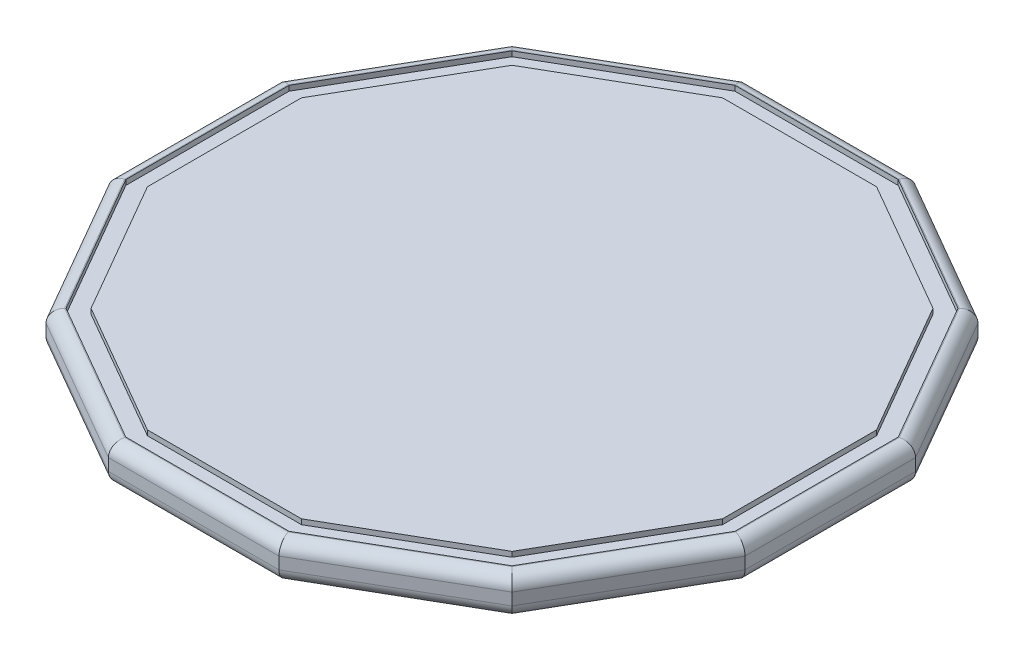
SolidWorks part; units mm, degrees
ref_plane "정면" through (0, 0, 0) normal (0, 0, 1) x (1, 0, 0)
ref_plane "윗면" through (0, 0, 0) normal (0, 1, 0) x (1, 0, 0)
ref_plane "우측면" through (0, 0, 0) normal (1, 0, 0) x (0, 0, -1)
sketch "스케치1" plane through (0, 0, 0) normal (0, 1, 0) x (1, 0, 0)
  line L1 (27.2932, -27.2932) -> (37.2832, -9.99)
  line L2 (37.2832, -9.99) -> (37.2832, 9.99)
  line L3 (37.2832, 9.99) -> (27.2932, 27.2932)
  line L4 (27.2932, 27.2932) -> (9.99, 37.2832)
  line L5 (9.99, 37.2832) -> (-9.99, 37.2832)
  line L6 (-9.99, 37.2832) -> (-27.2932, 27.2932)
  line L7 (-27.2932, 27.2932) -> (-37.2832, 9.99)
  line L8 (-37.2832, 9.99) -> (-37.2832, -9.99)
  line L9 (-37.2832, -9.99) -> (-27.2932, -27.2932)
  line L10 (-27.2932, -27.2932) -> (-9.99, -37.2832)
  line L11 (-9.99, -37.2832) -> (9.99, -37.2832)
  line L12 (9.99, -37.2832) -> (27.2932, -27.2932)
  circle A0 centre (0, 0) radius 37.2832 construction
  dimension "D1" = 19.98
extrude "보스-돌출1" add sketch "스케치1" along normal blind 4.4
sketch "스케치2" plane through (0, 4.4, 0) normal (0, 1, 0) x (1, 0, 0)
  line L0 (-26.1209, 26.1209) -> (-35.6818, 9.5609)
  line L1 (24.6568, -24.6568) -> (33.6818, -9.025)
  line L2 (33.6818, -9.025) -> (33.6818, 9.025)
  line L3 (33.6818, 9.025) -> (24.6568, 24.6568)
  line L4 (24.6568, 24.6568) -> (9.025, 33.6818)
  line L5 (9.025, 33.6818) -> (-9.025, 33.6818)
  line L6 (-9.025, 33.6818) -> (-24.6568, 24.6568)
  line L7 (-24.6568, 24.6568) -> (-33.6818, 9.025)
  line L8 (-33.6818, 9.025) -> (-33.6818, -9.025)
  line L9 (-33.6818, -9.025) -> (-24.6568, -24.6568)
  line L10 (-24.6568, -24.6568) -> (-9.025, -33.6818)
  line L11 (-9.025, -33.6818) -> (9.025, -33.6818)
  line L12 (9.025, -33.6818) -> (24.6568, -24.6568)
  line L13 (-35.6818, 9.5609) -> (-35.6818, -9.5609)
  line L14 (-35.6818, -9.5609) -> (-26.1209, -26.1209)
  line L15 (-26.1209, -26.1209) -> (-9.5609, -35.6818)
  line L16 (-9.5609, -35.6818) -> (9.5609, -35.6818)
  line L17 (9.5609, -35.6818) -> (26.1209, -26.1209)
  line L18 (26.1209, -26.1209) -> (35.6818, -9.5609)
  line L19 (35.6818, -9.5609) -> (35.6818, 9.5609)
  line L20 (35.6818, 9.5609) -> (26.1209, 26.1209)
  line L21 (26.1209, 26.1209) -> (9.5609, 35.6818)
  line L22 (9.5609, 35.6818) -> (-9.5609, 35.6818)
  line L23 (-9.5609, 35.6818) -> (-26.1209, 26.1209)
  circle A0 centre (0, 0) radius 33.6818 construction
  dimension "D1" = 18.05
  dimension "D2" = 2
extrude "컷-돌출1" cut sketch "스케치2" against normal blind 0.6
fillet "필렛1" radius 1.5 24 edges at (-32.2882, 0, 18.6416) (-37.2832, 0, 0) (-32.2882, 0, -18.6416) (-18.6416, 0, -32.2882) (0, 0, -37.2832) (18.6416, 0, -32.2882) (32.2882, 0, -18.6416) (-32.2882, 4.4, 18.6416) (-37.2832, 4.4, 0) (-32.2882, 4.4, -18.6416) (-18.6416, 4.4, -32.2882) (0, 4.4, -37.2832) (18.6416, 4.4, -32.2882) (32.2882, 4.4, -18.6416) (37.2832, 4.4, 0) (37.2832, 0, 0) (32.2882, 4.4, 18.6416) (32.2882, 0, 18.6416) (18.6416, 0, 32.2882) (18.6416, 4.4, 32.2882) (0, 0, 37.2832) (0, 4.4, 37.2832) (-18.6416, 0, 32.2882) (-18.6416, 4.4, 32.2882)
sketch "스케치3" plane through (0, 0, 0) normal (0, -1, 0) x (1, 0, 0)
  line L1 (-10, 7.5) -> (10, 7.5)
  line L2 (-10, 7.5) -> (-10, -7.5)
  line L3 (-10, -7.5) -> (10, -7.5)
  line L4 (10, 7.5) -> (10, -7.5)
  line L5 (-10, 7.5) -> (10, -7.5) construction
  line L6 (-10, -7.5) -> (10, 7.5) construction
  point P0 (0, 0)
  dimension "D1" = 20
  dimension "D2" = 15
extrude "보스-돌출2" add sketch "스케치3" along normal blind 10
sketch "스케치4" plane through (0, -10, 0) normal (0, -1, 0) x (1, 0, 0)
  line L0 (10, -7.5) -> (10, 7.5) construction
  line L1 (-10, 2.6) -> (10, 2.6)
  line L2 (-10, 2.6) -> (-10, -2.6)
  line L3 (-10, -2.6) -> (10, -2.6)
  line L4 (10, 2.6) -> (10, -2.6)
  line L5 (-10, 2.6) -> (10, -2.6) construction
  line L6 (-10, -2.6) -> (10, 2.6) construction
  point P0 (0, 0)
  dimension "D1" = 5.2
extrude "컷-돌출2" cut sketch "스케치4" against normal up to surface (10 mm away) up to face at (0, 0, 0)
sketch "스케치5" plane through (0, 0, -7.5) normal (0, 0, -1) x (-1, 0, 0)
  line L0 (0, 0) -> (0, -10) construction
  line L1 (10, -10) -> (-10, -10) construction
  line L2 (0, -5) -> (-5, -5) construction
  line L3 (0, -5) -> (5, -5) construction
  circle A0 centre (-5, -5) radius 1.6
  circle A1 centre (5, -5) radius 1.6
  dimension "D2" = 3.2
  dimension "D1" = 5
extrude "컷-돌출3" cut sketch "스케치5" against normal through all both and the other way through all
